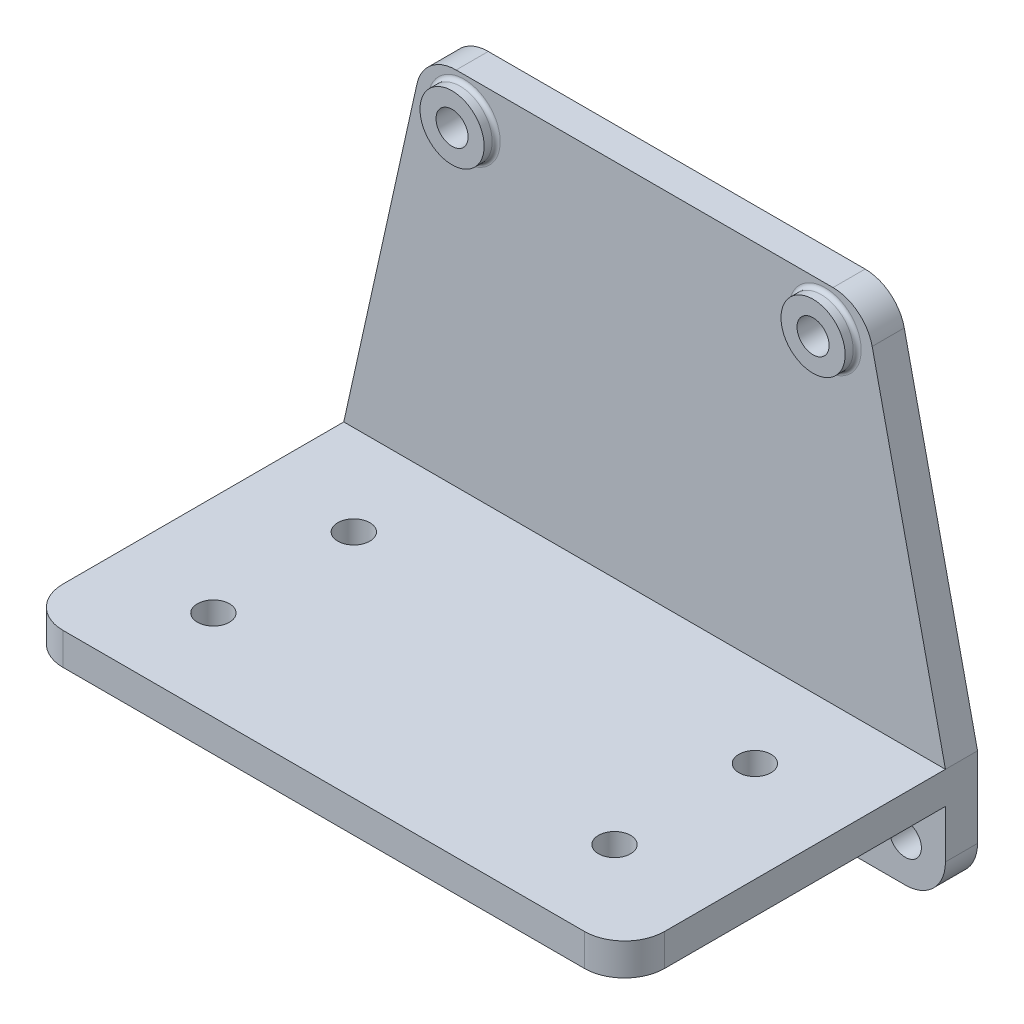
SolidWorks part; units mm, degrees
material "Сталь 40Х13 ГОСТ 5632-72"
ref_plane "Спереди" through (0, 0, 0) normal (0, 0, 1) x (1, 0, 0)
ref_plane "Сверху" through (0, 0, 0) normal (0, 1, 0) x (1, 0, 0)
ref_plane "Справа" through (0, 0, 0) normal (1, 0, 0) x (0, 0, -1)
sketch "Эскиз1" plane through (0, 0, 0) normal (0, 0, 1) x (1, 0, 0)
  line L0 (0, 0) -> (75, 0)
  line L1 (75, 0) -> (75, 30)
  line L2 (75, 30) -> (55, 120)
  line L3 (55, 120) -> (0, 120)
  line L4 (0, 120) -> (0, 0)
  line L5 (0, 0) -> (0, 148.6143) construction
  dimension "D1" = 75
  dimension "D2" = 120
  dimension "D3" = 30
  dimension "D4" = 55
extrude "Бобышка-Вытянуть1" add sketch "Эскиз1" along normal blind 8
sketch "Эскиз2" plane through (0, 0, 8) normal (0, 0, 1) x (1, 0, 0)
  line L0 (0, 120) -> (0, 0) construction
  line L1 (0, 0) -> (75, 0) construction
  line L3 (55, 120) -> (0, 120) construction
  circle A0 centre (45, 110) radius 4
  circle A1 centre (0, 10) radius 4
  circle A2 centre (65, 10) radius 4
  dimension "D2" = 8
  dimension "D3" = 65
  dimension "D4" = 10
  dimension "D5" = 10
  dimension "D1" = 45
extrude "Вырез-Вытянуть1" cut sketch "Эскиз2" against normal through all
sketch "Эскиз3" plane through (0, 0, 8) normal (0, 0, 1) x (1, 0, 0)
  line L0 (0, 120) -> (0, 14) construction
  line L1 (75, 30) -> (0, 30)
  line L2 (75, 30) -> (75, 22)
  line L3 (75, 22) -> (0, 22)
  line L4 (0, 30) -> (0, 22)
  dimension "D1" = 8
extrude "Бобышка-Вытянуть2" add sketch "Эскиз3" along normal blind 80
sketch "Эскиз5" plane through (0, 30, 0) normal (0, 1, 0) x (1, 0, 0)
  line L0 (75, -48) -> (0, -48) construction
  line L1 (75, -88) -> (75, -8) construction
  line L2 (0, -88) -> (0, -8) construction
  line L4 (0, -88) -> (0, 0) construction
  circle A0 centre (50, -30.5) radius 4
  circle A1 centre (50, -65.5) radius 4
  dimension "D1" = 8
  dimension "D2" = 100
  dimension "D3" = 35
extrude "Вырез-Вытянуть2" cut sketch "Эскиз5" against normal through all
ref_plane "Плоскость1" through (35, 0, 0) normal (1, 0, 0) x (0, 0, -1)
sketch "Эскиз6" plane through (35, 0, 0) normal (1, 0, 0) x (0, 0, -1)
  line L0 (-88, 22) -> (-8, 0)
  line L1 (-8, 0) -> (-8, 22) construction
rib "Ребро1" sketch "Эскиз6" sketch "Эскиз6" thickness 8 extrusion direction parallel to sketch draft on no parameters "D1"=8
fillet "Скругление2" radius 10 3 edges at (55, 120, 4) (75, 0, 4) (75, 26, 88)
mirror "Зеркальное отражение1" about plane through (0, 120, 8) normal (1, 0, 0) of bodies 108
sketch "Эскиз7" plane through (0, 0, 8) normal (0, 0, 1) x (1, 0, 0)
  circle A0 centre (-45, 110) radius 8
  circle A1 centre (-45, 110) radius 4 construction
  circle A2 centre (45, 110) radius 4 construction
  circle A3 centre (-45, 110) radius 4
  circle A4 centre (45, 110) radius 4
  circle A5 centre (45, 110) radius 8
  dimension "D1" = 16
extrude "Бобышка-Вытянуть3" add sketch "Эскиз7" along normal blind 3
fillet "Скругление3" radius 1 2 edges at (53, 110, 8) (-37, 110, 8)
fillet "Скругление4" radius 8 7 edges at (-39, 11, 8) (-31, 11, 8) (31, 11, 8) (39, 11, 8)
